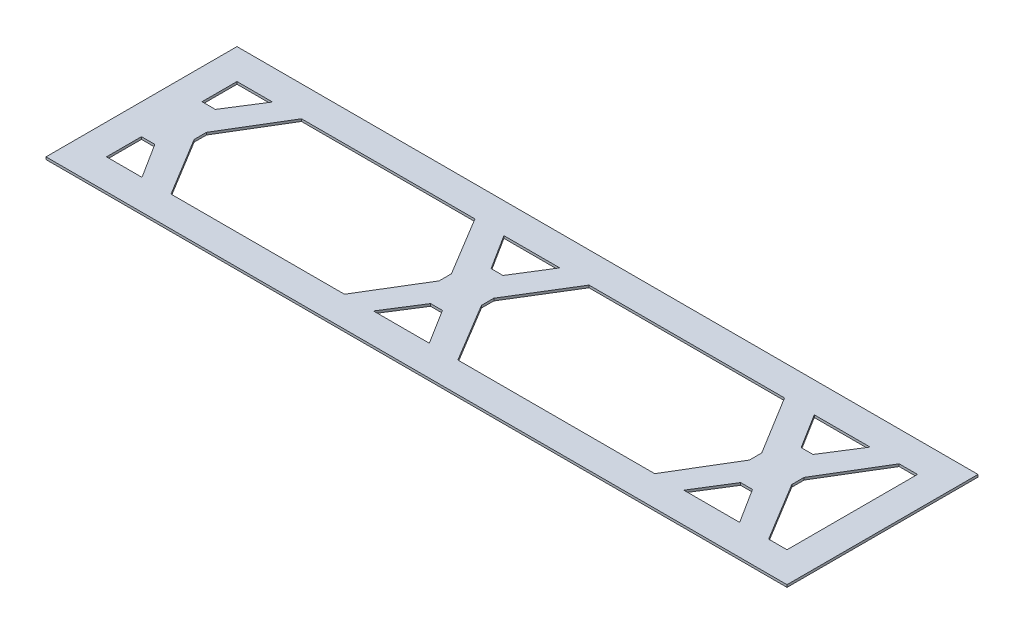
SolidWorks part; units mm, degrees
ref_plane "Front Plane" through (0, 0, 0) normal (0, 0, 1) x (1, 0, 0)
ref_plane "Top Plane" through (0, 0, 0) normal (0, 1, 0) x (1, 0, 0)
ref_plane "Right Plane" through (0, 0, 0) normal (1, 0, 0) x (0, 0, -1)
sketch "Sketch1" plane through (0, 0, 0) normal (0, 1, 0) x (1, 0, 0)
  line L0 (12.7, 52.8066) -> (18.3108, 52.8066)
  line L1 (311.15, 80.1913) -> (311.15, 0)
  line L2 (311.15, 80.1913) -> (0, 80.1913)
  line L3 (0, 80.1913) -> (0, 0)
  line L4 (311.15, 0) -> (0, 0)
  line L5 (18.3108, 52.8066) -> (27.6092, 67.4913)
  line L6 (27.6092, 67.4913) -> (12.7, 67.4913)
  line L7 (12.7, 67.4913) -> (12.7, 52.8066)
  line L8 (12.7, 12.7) -> (27.6092, 12.7)
  line L9 (27.6092, 12.7) -> (18.3108, 27.3847)
  line L10 (18.3108, 27.3847) -> (12.7, 27.3847)
  line L11 (12.7, 27.3847) -> (12.7, 12.7)
  line L12 (39.785, 12.7) -> (112.615, 12.7)
  line L13 (112.615, 12.7) -> (127.635, 37.4247)
  line L14 (127.635, 37.4247) -> (127.635, 42.5993)
  line L15 (127.635, 42.5993) -> (112.615, 67.4913)
  line L16 (112.615, 67.4913) -> (39.785, 67.4913)
  line L17 (39.785, 67.4913) -> (24.765, 42.5993)
  line L18 (134.0892, 27.3847) -> (139.0819, 27.3847)
  line L19 (24.765, 42.5993) -> (24.765, 37.4247)
  line L20 (24.765, 37.4247) -> (39.785, 12.7)
  line L21 (124.7908, 67.4913) -> (134.0892, 52.8066)
  line L22 (134.0892, 52.8066) -> (139.0819, 52.8066)
  line L23 (139.0819, 52.8066) -> (148.2429, 67.4913)
  line L24 (148.2429, 67.4913) -> (124.7908, 67.4913)
  line L25 (139.0819, 27.3847) -> (148.2429, 12.7)
  line L26 (148.2429, 12.7) -> (124.7908, 12.7)
  line L27 (124.7908, 12.7) -> (134.0892, 27.3847)
  line L28 (160.6259, 67.3768) -> (242.7261, 67.3768)
  line L29 (242.7261, 67.3768) -> (257.937, 42.5993)
  line L30 (257.937, 42.5993) -> (257.937, 37.4247)
  line L31 (257.937, 37.4247) -> (242.9874, 12.5861)
  line L32 (242.9874, 12.5861) -> (160.3646, 12.5861)
  line L33 (160.3646, 12.5861) -> (145.415, 37.4247)
  line L34 (145.415, 37.4247) -> (145.415, 42.5993)
  line L35 (145.415, 42.5993) -> (160.6259, 67.3768)
  line L36 (255.1091, 67.4913) -> (264.2701, 52.8066)
  line L37 (264.2701, 52.8066) -> (269.2628, 52.8066)
  line L38 (269.2628, 52.8066) -> (278.5612, 67.4913)
  line L39 (278.5612, 67.4913) -> (255.1091, 67.4913)
  line L40 (264.2701, 27.3847) -> (269.2628, 27.3847)
  line L41 (269.2628, 27.3847) -> (278.5612, 12.7)
  line L42 (278.5612, 12.7) -> (255.1091, 12.7)
  line L43 (255.1091, 12.7) -> (264.2701, 27.3847)
  line L44 (298.45, 67.4913) -> (298.45, 12.7)
  line L45 (298.45, 12.7) -> (290.737, 12.7)
  line L46 (290.737, 12.7) -> (275.717, 37.4247)
  line L47 (275.717, 37.4247) -> (275.717, 42.5993)
  line L48 (275.717, 42.5993) -> (290.737, 67.4913)
  line L49 (290.737, 67.4913) -> (298.45, 67.4913)
extrude "Boss-Extrude1" add sketch "Sketch1" along normal blind 1
